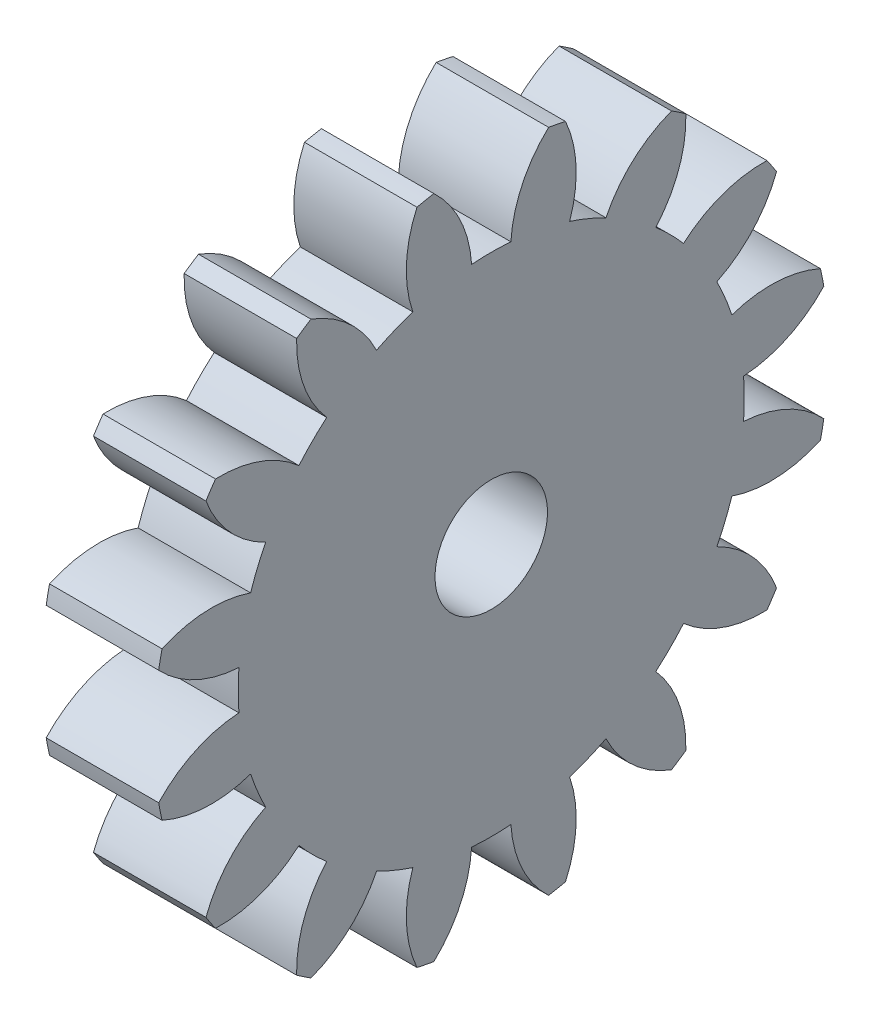
SolidWorks part; units mm, degrees
ref_plane "Plane1" through (0, 0, 0) normal (0, 0, 1) x (1, 0, 0)
ref_plane "Plane2" through (0, 0, 0) normal (0, 1, 0) x (1, 0, 0)
ref_plane "Plane3" through (0, 0, 0) normal (1, 0, 0) x (0, 0, -1)
sketch "HoldingSke" plane through (0, 0, 0) normal (0, 1, 0) x (1, 0, 0)
  line L0 (0, 0) -> (0.9613, -0.2756)
  line L1 (-15, 0) -> (100, 0) construction
  line L2 (0, 0) -> (-2.1039, 2.3779)
  line L3 (0, 0) -> (-11.863, 4.5341)
  line L4 (0, 0) -> (8.3015, 2.3804)
  line L5 (0, 0) -> (-14.0543, -5.2418)
  line L6 (0, 0) -> (-2.4869, -1.6779)
  line L7 (-2.1039, 2.3779) -> (1.1249, 17.0263)
  line L8 (-76.2, 54.61) -> (-75.7, 54.61)
  line L9 (-71.009, 38.7566) -> (-53.1078, 45.2721)
  line L10 (-76.2, 71.12) -> (104.1128, 71.12)
  line L11 (0, 0) -> (-3, 0)
  line L12 (-76.2, 101.6) -> (-76.162, 101.6)
  line L13 (24.9733, 27.94) -> (52.9518, 28.4284)
  line L14 (24.9733, 27.94) -> (24.9743, 27.94)
  line L15 (24.9733, 27.94) -> (100.4006, 29.5858)
  line L16 (-63.627, -1) -> (-12.827, -1)
  circle A0 centre (0, 0) radius 1.5
  circle A1 centre (0, 0) radius 2.5
  circle A2 centre (0, 0) radius 2.5
  circle A3 centre (0, 0) radius 1.5
  dimension "MHD" = 5
  dimension "Hub_dia" = 5
  dimension "Bore" = 3
  dimension "MBD" = 3
  dimension "Num_teeth" = 16
  dimension "Pitch_radius" = 180.3128
  dimension "Pitch" = 1
  dimension "Width" = 3
  dimension "Overall_len" = 15
  dimension "Show_teeth" = 16
  dimension "Thickness" = 3
  dimension "OAL" = 15.0001
  dimension "T_dim" = 0.5
  dimension "Ap" = 20
  dimension "H" = 19.05
  dimension "Backlash" = 0.038
  dimension "Addendum_fac" = 1
  dimension "Dedendum_fac" = 1.25
  dimension "Clearance_fac" = 0.25
  dimension "Dedendum_add" = 0.001
  dimension "Module" = 1
sketch "BasProSke" plane through (0, 0, 0) normal (0, 1, 0) x (1, 0, 0)
  line L0 (-10, 0) -> (60, 0) construction
  line L1 (0, 0) -> (0, 9)
  line L2 (0, 0) -> (3, 0)
  line L3 (3, 0) -> (3, 9)
  line L4 (3, 9) -> (0, 9)
  dimension "Diameter" = 18
  dimension "Thickness" = 3
revolve "Base-Revolve" add sketch "BasProSke" angle 360 about L0
sketch "TooCutSke" plane through (0, 0, 0) normal (1, 0, 0) x (0, 0, -1)
  line L1 (0, 0) -> (0, 107) construction
  line L2 (0, 0) -> (-0.8506, 7.9547) construction
  line L3 (0, 0) -> (-3.1089, 15.6293) construction
  line L4 (-0.8506, 7.9547) -> (-1.5544, 7.8146) construction
  arc A0 (0.5238, 6.7286) -> (-0.5238, 6.7286) centre (0, 0) ccw
  arc A1 (1.5534, 8.8907) -> (-1.5534, 8.8907) centre (0, 0) ccw
  circle A2 centre (0, 0) radius 8 construction
  circle A3 centre (0, 0) radius 7.5175 construction
  arc A4 (-0.5238, 6.7286) -> (-1.5534, 8.8907) centre (-3.7179, 6.5338) ccw
  arc A5 (1.5534, 8.8907) -> (0.5238, 6.7286) centre (3.7179, 6.5338) ccw
  dimension "Root_dia" = 13.498
  dimension "Overcut_dia" = 18.0508
  dimension "Pitch_dia" = 16
  dimension "Base_dia" = 15.0351
  dimension "Flank_rad" = 3.2
  dimension "Half_ang" = 11.25
  dimension "Half_CT" = 0.7176
extrude "ToothCut" cut sketch "TooCutSke" along normal through all
fillet "Breaks" [suppressed] radius 0.02
fillet "RootFillets" [suppressed] radius 0.251
pattern_circular "TeethCuts" count 16 every 22.5 about axis through (-10, 0, 0) along (1, 0, 0) of "ToothCut", "RootFillets", "Breaks"
sketch "HubNeaOneSke" plane through (0, 0, 0) normal (-1, 0, 0) x (0, 0, 1)
  circle A0 centre (0, 0) radius 2.5
  dimension "Diameter" = 5
extrude "HubNearOne" [suppressed] add sketch "HubNeaOneSke" along normal blind 12.0001
sketch "HubNeaBotSke" plane through (0, 0, 0) normal (-1, 0, 0) x (0, 0, 1)
  circle A0 centre (0, 0) radius 2.5
  dimension "Diameter" = 5
extrude "HubNearBoth" [suppressed] add sketch "HubNeaBotSke" along normal blind 6
ref_plane "FarPln" through (3, 0, 0) normal (1, 0, 0) x (0, 0, -1)
sketch "HubFarSke" plane through (3, 0, 0) normal (1, 0, 0) x (0, 0, -1)
  circle A0 centre (0, 0) radius 2.5
  dimension "Diameter" = 5
extrude "HubFar" [suppressed] add sketch "HubFarSke" along normal blind 6
sketch "BorSke" plane through (0, 0, 0) normal (1, 0, 0) x (0, 0, -1)
  circle A0 centre (0, 0) radius 1.5
  dimension "Diameter" = 3
extrude "Bore" cut sketch "BorSke" along normal mid plane 30.0001
sketch "KeySke" plane through (0, 0, 0) normal (1, 0, 0) x (0, 0, -1)
  line L0 (-0.6, 0) -> (-0.6, 2)
  line L1 (-0.6, 2) -> (0.6, 2)
  line L2 (0.6, 2) -> (0.6, 0)
  line L3 (0, 0) -> (0, 34) construction
  line L4 (-0.6, 0) -> (0.6, 0)
  dimension "Offset" = 2
  dimension "Width" = 1.2
extrude "Keyway" [suppressed] cut sketch "KeySke" along normal mid plane 30.0001
pattern_circular "Keyway2" [suppressed] count 2 every 90 about axis through (-10, 0, 0) along (1, 0, 0)
equation "' \"Module@HoldingSke\" = 6.35"
equation "' \"Num_teeth@HoldingSke\" = 12"
equation "' \"Ap@HoldingSke\" =  20"
equation "' \"Width@HoldingSke\" = 0.5 * 25.4"
equation "' \"Hub_dia@HoldingSke\"= 1 * 25.4"
equation "' \"Overall_len@HoldingSke\" = 1.0 * 25.4"
equation "' \"Bore@HoldingSke\" = 0.75 * 25.4"
equation "' \"T_dim@HoldingSke\" = 0.1 * 25.4"
equation "' \"Width@KeySke\" = 0.25 * 25.4"
equation "' \"Show_teeth@HoldingSke\" = 13"
equation "' \"Backlash@HoldingSke\" = 0.009 * 25.4"
equation "' \"Addendum_fac@HoldingSke\" = 1.0"
equation "' \"Dedendum_fac@HoldingSke\" = 1.25"
equation "' \"Dedendum_add@HoldingSke\" = 0.00005 * 25.4"
equation "' \"Clearance_fac@HoldingSke\" = 0.25"
equation "\"Pitch@HoldingSke\" = 1 / \"Module@HoldingSke\""
equation "\"Overcut_dia@TooCutSke\" = (\"Num_teeth@HoldingSke\" + 2 * \"Addendum_fac@HoldingSke\") / \"Pitch@HoldingSke\" + 0.002 * 25.4"
equation "\"Pitch_dia@TooCutSke\" = \"Num_teeth@HoldingSke\" / \"Pitch@HoldingSke\""
equation "\"Base_dia@TooCutSke\" = \"Num_teeth@HoldingSke\" / \"Pitch@HoldingSke\" * cos((\"Ap@HoldingSke\"  * 3.14159265 / 180))"
equation "\"Root_dia@TooCutSke\" = (\"Num_teeth@HoldingSke\" + 2) / \"Pitch@HoldingSke\" - 2 * (\"Addendum_fac@HoldingSke\" + \"Dedendum_fac@HoldingSke\") / \"Pitch@HoldingSke\" - \"Dedendum_add@HoldingSke\" * 2"
equation "\"Half_ang@TooCutSke\" = 180 / \"Num_teeth@HoldingSke\""
equation "\"Half_CT@TooCutSke\" = \"Num_teeth@HoldingSke\" / \"Pitch@HoldingSke\" * sin((3.14159265 / 2 / \"Num_teeth@HoldingSke\")) / 2 - 7 * \"Backlash@HoldingSke\" / 4"
equation "\"Flank_rad@TooCutSke\" = \"Num_teeth@HoldingSke\" / \"Pitch@HoldingSke\" / 5"
equation "\"Radius@RootFillets\" = \"Clearance_fac@HoldingSke\" / \"Pitch@HoldingSke\" + \"Dedendum_add@HoldingSke\""
equation "\"Break_rad@Breaks\" = 0.02 / \"Pitch@HoldingSke\""
equation "\"Thickness@HoldingSke\" = \"Width@HoldingSke\""
equation "\"OAL@HoldingSke\" = \"Thickness@HoldingSke\""
equation "\"MHD@HoldingSke\" = (\"Num_teeth@HoldingSke\" + 2) / \"Pitch@HoldingSke\" - 2 * (\"Addendum_fac@HoldingSke\" + \"Dedendum_fac@HoldingSke\")  / \"Pitch@HoldingSke\" - \"Dedendum_add@HoldingSke\" * 2"
equation "\"MBD@HoldingSke\" = (\"Num_teeth@HoldingSke\" + 2) / \"Pitch@HoldingSke\" - 2 * (\"Addendum_fac@HoldingSke\" + \"Dedendum_fac@HoldingSke\")  / \"Pitch@HoldingSke\" - \"Dedendum_add@HoldingSke\" * 2 - 0.002 * 25.4"
equation "\"MHD@HoldingSke\" = ((sgn( \"MHD@HoldingSke\" - \"Hub_dia@HoldingSke\" )-1)*( \"MHD@HoldingSke\" - \"Hub_dia@HoldingSke\" ))/-2+ \"Hub_dia@HoldingSke\""
equation "\"MBD@HoldingSke\" = ((sgn( \"MBD@HoldingSke\" - \"Bore@HoldingSke\" )-1)*( \"MBD@HoldingSke\" - \"Bore@HoldingSke\" ))/-2+ \"Bore@HoldingSke\""
equation "\"OAL@HoldingSke\" = ((sgn( \"OAL@HoldingSke\" - \"Overall_len@HoldingSke\" )+1)*( \"OAL@HoldingSke\" - \"Overall_len@HoldingSke\" ))/2 + \"Overall_len@HoldingSke\" + 0.000002 * 25.4"
equation "\"Num_teeth@TeethCuts\" = int( \"Show_teeth@HoldingSke\" ) + 1"
equation "\"Num_teeth@TeethCuts\" = ((sgn( \"Num_teeth@TeethCuts\" - \"Num_teeth@HoldingSke\" )-1)*( \"Num_teeth@TeethCuts\" - \"Num_teeth@HoldingSke\" ))/-2+ \"Num_teeth@HoldingSke\""
equation "\"Num_teeth@TeethCuts\" = ((sgn( \"Num_teeth@TeethCuts\" - 2.0)+1)*( \"Num_teeth@TeethCuts\" - 2.0))/2 +2.0"
equation "\"Angle@TeethCuts\" = 360.0 / \"Num_teeth@HoldingSke\""
equation "\"Diameter@BasProSke\" = (\"Num_teeth@HoldingSke\" + 2 * \"Addendum_fac@HoldingSke\") / \"Pitch@HoldingSke\""
equation "\"Thickness@BasProSke\"  = \"Thickness@HoldingSke\""
equation "' \"Fillet_rad@BasProSke\" =  \"Thickness@HoldingSke\" * 0.05"
equation "\"MHD@HoldingSke\" = ((sgn( \"MHD@HoldingSke\" - \"Root_dia@TooCutSke\" )-1)*( \"MHD@HoldingSke\" - \"Root_dia@TooCutSke\" ))/-2+ \"Root_dia@TooCutSke\""
equation "\"Diameter@HubNeaOneSke\" = \"MHD@HoldingSke\""
equation "\"Length@HubNearOne\" = \"OAL@HoldingSke\" - \"Thickness@BasProSke\""
equation "\"Diameter@HubNeaBotSke\" = \"MHD@HoldingSke\""
equation "\"Length@HubNearBoth\" = ( \"OAL@HoldingSke\" - \"Thickness@BasProSke\" ) / 2.0"
equation "\"Thickness@FarPln\" = \"Thickness@BasProSke\""
equation "\"Diameter@HubFarSke\" = \"MHD@HoldingSke\""
equation "\"Length@HubFar\" = ( \"OAL@HoldingSke\" - \"Thickness@BasProSke\" ) / 2.0"
equation "\"Diameter@BorSke\" = \"MBD@HoldingSke\""
equation "\"D1@Bore\" = \"OAL@HoldingSke\" * 2.0"
equation "\"D1@Keyway\" = \"OAL@HoldingSke\" * 2.0"
equation "\"Offset@KeySke\" = \"T_dim@HoldingSke\" + \"MBD@HoldingSke\" / 2.0"
